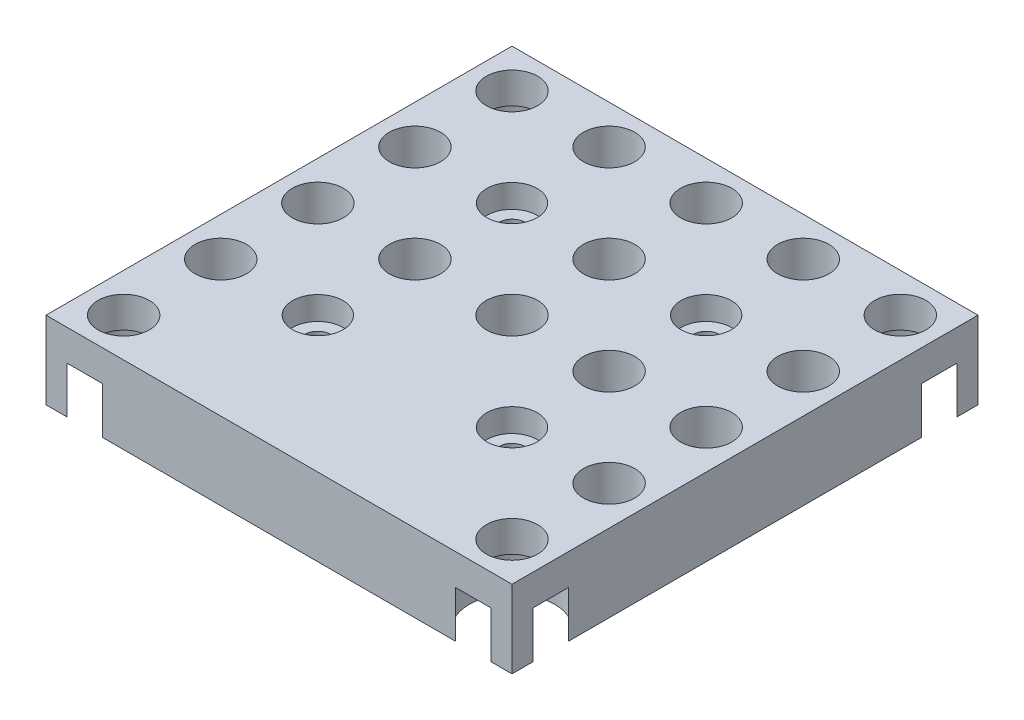
SolidWorks part; units mm, degrees
ref_plane "Front Plane" through (0, 0, 0) normal (0, 0, 1) x (1, 0, 0)
ref_plane "Top Plane" through (0, 0, 0) normal (0, 1, 0) x (1, 0, 0)
ref_plane "Right Plane" through (0, 0, 0) normal (1, 0, 0) x (0, 0, -1)
sketch "Sketch1" plane through (0, 0, 0) normal (0, 1, 0) x (1, 0, 0)
  line L1 (-30, -30) -> (30, -30)
  line L2 (-30, -30) -> (-30, 30)
  line L3 (-30, 30) -> (30, 30)
  line L4 (30, -30) -> (30, 30)
  line L5 (-30, -30) -> (30, 30) construction
  line L6 (-30, 30) -> (30, -30) construction
  point P0 (0, 0)
  dimension "D1" = 60
  dimension "D2" = 60
extrude "Extrude1" add sketch "Sketch1" along normal blind 10
sketch "Sketch3" plane through (0, 10, 0) normal (0, 1, 0) x (-1, 0, 0)
  line L0 (37.1198, 0) -> (-42.4335, 0) construction
  line L1 (0, -35.1244) -> (0, 34.194) construction
hole_wizard "CBORE for M3 SHCS1" positions "3DSketch2" profile "Sketch4" counterbore size "M3" standard "Ansi Metric" end condition through all
sketch3d "3DSketch2"
  line L0 (0, 10, -35.1244) -> (0, 10, 34.194) construction
  line L1 (-37.1198, 10, 0) -> (42.4335, 10, 0) construction
  point P0 (-12.5, 10, -12.5)
  dimension "D1" = 12.5
  dimension "D2" = 12.5
sketch "Sketch4" plane through (-12.5, 10, -12.5) normal (1, 0, 0) x (0, 0, 1)
  line L0 (0, 0) -> (0, 10)
  line L1 (0, 10) -> (1.7, 10)
  line L3 (1.7, 10) -> (1.7, 3)
  line L4 (1.7, 3) -> (3.25, 3)
  line L5 (3.25, 3) -> (3.25, 0)
  line L7 (3.25, 0) -> (0, 0)
  line L11 (0, -6.35) -> (0, 107.95) construction
  dimension "Thru Hole Dia." = 3.4
  dimension "Thru Hole Depth" = 10
  dimension "C'Bore Dia." = 6.5
  dimension "C'Bore Depth" = 3
pattern_linear "LPattern2" count 2 spacing 25 along (0, 0, 1) count 2 spacing 25 along (1, 0, 0) of "CBORE for M3 SHCS1"
sketch "Sketch5" plane through (0, 0, 0) normal (0, -1, 0) x (1, 0, 0)
  line L0 (42.1228, 0) -> (-46.7742, 0) construction
  line L1 (0, -35.5623) -> (0, 38.5451) construction
hole_wizard "CBORE for M6 SHCS1" positions "3DSketch3" profile "Sketch6" counterbore size "M6" standard "Ansi Metric" end condition through all
sketch3d "3DSketch3"
  line L0 (0, 0, -35.5623) -> (0, 0, 38.5451) construction
  line L1 (42.1228, 0, 0) -> (-46.7742, 0, 0) construction
  point P0 (25, 0, -25)
  dimension "D1" = 25
  dimension "D2" = 25
sketch "Sketch6" plane through (25, 0, -25) normal (1, 0, 0) x (0, 0, -1)
  line L0 (0, 0) -> (0, 10)
  line L1 (0, 10) -> (3.3, 10)
  line L3 (3.3, 10) -> (3.3, 6)
  line L4 (3.3, 6) -> (5.5, 6)
  line L5 (5.5, 6) -> (5.5, 0)
  line L7 (5.5, 0) -> (0, 0)
  line L11 (0, -6.35) -> (0, 107.95) construction
  dimension "Thru Hole Dia." = 6.6
  dimension "Thru Hole Depth" = 10
  dimension "C'Bore Dia." = 11
  dimension "C'Bore Depth" = 6
pattern_linear "LPattern3" count 2 spacing 50 along (-1, 0, 0) count 2 spacing 50 along (0, 0, 1) of "CBORE for M6 SHCS1"
hole_wizard "M6 Clearance Hole1" positions "3DSketch4" profile "Sketch7" hole size "M6" standard "Ansi Metric"
sketch3d "3DSketch4"
  line L0 (0, 0, -35.5623) -> (0, 0, 38.5451) construction
  point P0 (0, 0, -25)
  dimension "D1" = 25
sketch "Sketch7" plane through (0, 0, -25) normal (1, 0, 0) x (0, 0, -1)
  line L0 (0, 0) -> (0, 11.9828)
  line L1 (0, 11.9828) -> (3.3, 10)
  line L2 (3.3, 10) -> (3.3, 0)
  line L5 (3.3, 0) -> (0, 0)
  line L10 (0, 11.9828) -> (-3.3, 10) construction
  line L11 (0, -6.35) -> (0, 107.95) construction
  dimension "Hole Dia." = 6.6
  dimension "Hole Depth" = 10
  dimension "Drill Angle" = 118
pattern_linear "LPattern5" count 2 spacing 12.5 along (-1, 0, 0) count 2 spacing 12.5 along (1, 0, 0) of "M6 Clearance Hole1"
pattern_linear "LPattern6" count 2 spacing 12.5 along (0, 0, 1) of "M6 Clearance Hole1"
hole_wizard "M6 Clearance Hole2" positions "3DSketch6" profile "Sketch9" hole size "M6" standard "Ansi Metric"
sketch3d "3DSketch6"
  line L0 (42.1228, 0, 0) -> (-46.7742, 0, 0) construction
  point P0 (0, 0, 0)
  point P4 (25, 0, 0)
  dimension "D1" = 25
sketch "Sketch9" plane through (25, 0, 0) normal (1, 0, 0) x (0, 0, -1)
  line L0 (0, 0) -> (0, 11.9828)
  line L1 (0, 11.9828) -> (3.3, 10)
  line L2 (3.3, 10) -> (3.3, 0)
  line L5 (3.3, 0) -> (0, 0)
  line L10 (0, 11.9828) -> (-3.3, 10) construction
  line L11 (0, -6.35) -> (0, 107.95) construction
  dimension "Hole Dia." = 6.6
  dimension "Hole Depth" = 10
  dimension "Drill Angle" = 118
pattern_linear "LPattern7" count 2 spacing 12.5 along (0, 0, 1) count 2 spacing 12.5 along (0, 0, -1) of "M6 Clearance Hole2"
pattern_linear "LPattern8" count 3 spacing 12.5 along (-1, 0, 0) of "M6 Clearance Hole2"
hole_wizard "M6 Clearance Hole3" positions "3DSketch7" profile "Sketch10" hole size "M6" standard "Ansi Metric"
sketch3d "3DSketch7"
  line L0 (42.1228, 0, 0) -> (-46.7742, 0, 0) construction
  point P0 (-25, 0, 0)
  dimension "D1" = 25
sketch "Sketch10" plane through (-25, 0, 0) normal (1, 0, 0) x (0, 0, -1)
  line L0 (0, 0) -> (0, 11.9828)
  line L1 (0, 11.9828) -> (3.3, 10)
  line L2 (3.3, 10) -> (3.3, 0)
  line L5 (3.3, 0) -> (0, 0)
  line L10 (0, 11.9828) -> (-3.3, 10) construction
  line L11 (0, -6.35) -> (0, 107.95) construction
  dimension "Hole Dia." = 6.6
  dimension "Hole Depth" = 10
  dimension "Drill Angle" = 118
pattern_linear "LPattern9" count 2 spacing 12.5 along (0, 0, 1) count 2 spacing 12.5 along (0, 0, -1) of "M6 Clearance Hole3"
pattern_linear "LPattern10" count 2 spacing 12.5 along (1, 0, 0) of "M6 Clearance Hole3"
